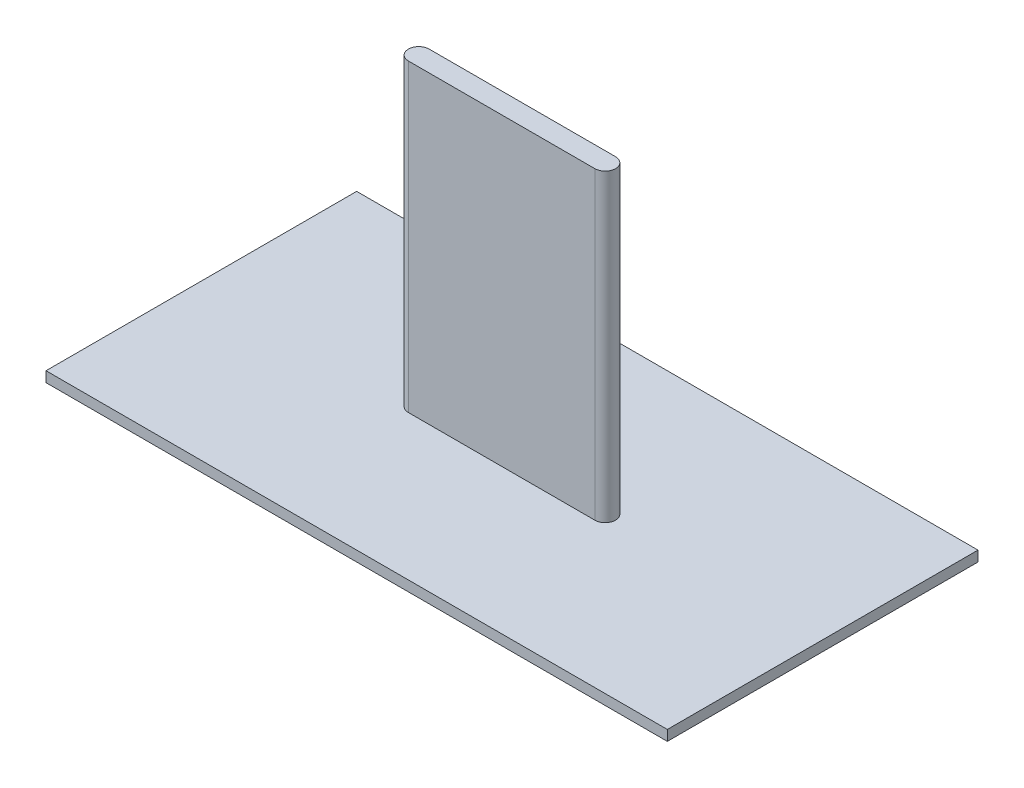
SolidWorks part; units mm, degrees
material "Plain Carbon Steel"
ref_plane "Front Plane" through (0, 0, 0) normal (0, 0, 1) x (1, 0, 0)
ref_plane "Top Plane" through (0, 0, 0) normal (0, 1, 0) x (1, 0, 0)
ref_plane "Right Plane" through (0, 0, 0) normal (1, 0, 0) x (0, 0, -1)
sketch "Sketch1" plane through (0, 0, 0) normal (0, 1, 0) x (1, 0, 0)
  line L1 (-150, -75) -> (150, -75)
  line L2 (-150, -75) -> (-150, 75)
  line L3 (-150, 75) -> (150, 75)
  line L4 (150, -75) -> (150, 75)
  line L5 (-150, -75) -> (150, 75) construction
  line L6 (-150, 75) -> (150, -75) construction
  point P0 (0, 0)
  dimension "D1" = 150
  dimension "D2" = 300
extrude "Boss-Extrude1" add sketch "Sketch1" along normal blind 5
sketch "Sketch2" plane through (0, 5, 0) normal (0, 1, 0) x (1, 0, 0)
  line L0 (-45, 0) -> (45, 0) construction
  line L5 (-45, 5) -> (45, 5)
  line L6 (-45, -5) -> (45, -5)
  arc A0 (-45, 5) -> (-45, -5) centre (-45, 0) ccw
  arc A1 (45, -5) -> (45, 5) centre (45, 0) ccw
  point P2 (0, 0)
  dimension "D1" = 90
  dimension "D2" = 10
extrude "Boss-Extrude2" add sketch "Sketch2" along normal blind 147
